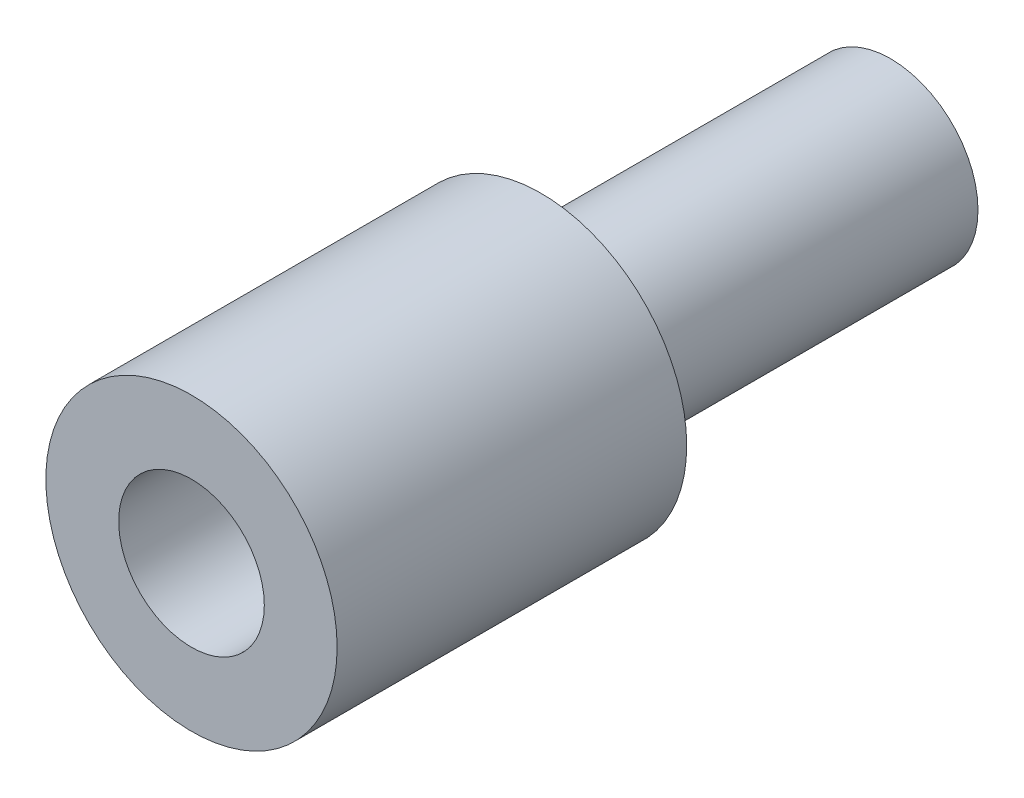
SolidWorks part; units mm, degrees
ref_plane "Front Plane" through (0, 0, 0) normal (0, 0, 1) x (1, 0, 0)
ref_plane "Top Plane" through (0, 0, 0) normal (0, 1, 0) x (1, 0, 0)
ref_plane "Right Plane" through (0, 0, 0) normal (1, 0, 0) x (0, 0, -1)
sketch "Sketch1" plane through (0, 0, 0) normal (0, 0, 1) x (1, 0, 0)
  circle A0 centre (0, 0) radius 1.5
  dimension "D1" = 3
extrude "Boss-Extrude1" add sketch "Sketch1" along normal blind 6
sketch "Sketch2" plane through (0, 0, 6) normal (0, 0, 1) x (1, 0, 0)
  circle A0 centre (0, 0) radius 2.5
  dimension "D1" = 5
extrude "Boss-Extrude2" add sketch "Sketch2" along normal blind 6
sketch "Sketch3" plane through (0, 0, 12) normal (0, 0, 1) x (1, 0, 0)
  circle A0 centre (0, 0) radius 1.25
  dimension "D1" = 2.5
extrude "Cut-Extrude1" cut sketch "Sketch3" against normal blind 6
